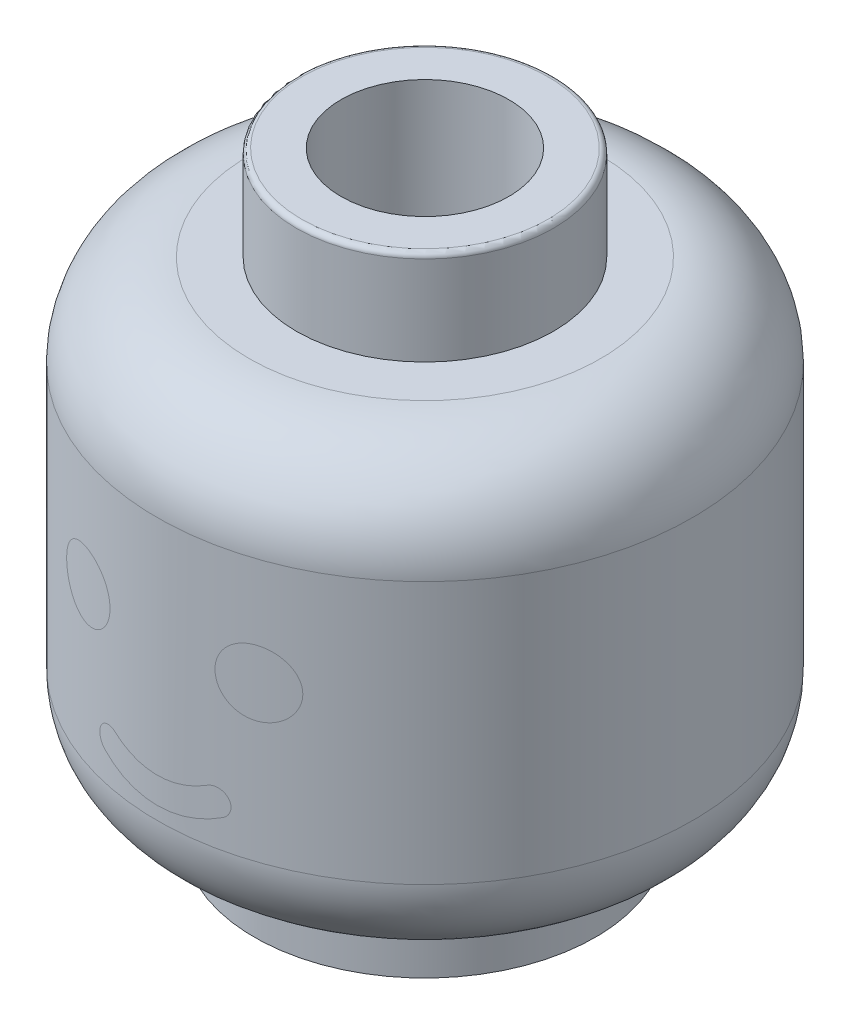
SolidWorks part; units mm, degrees
ref_plane "Plan de face" through (0, 0, 0) normal (0, 0, 1) x (1, 0, 0)
ref_plane "Plan de dessus" through (0, 0, 0) normal (0, 1, 0) x (1, 0, 0)
ref_plane "Plan de droite" through (0, 0, 0) normal (1, 0, 0) x (0, 0, -1)
sketch "Sketch2" plane through (0, 0, 0) normal (1, 0, 0) x (0, 0, -1)
  line L0 (0, 0) -> (0, 8.5) construction
  line L1 (2.45, 0) -> (3.25, 0)
  line L2 (3.25, 0) -> (3.25, 1.1)
  line L3 (3.25, 1.1) -> (3.35, 1.1)
  line L4 (5.1, 2.85) -> (5.1, 7.85)
  line L5 (3.35, 9.6) -> (2.45, 9.6)
  line L6 (2.45, 9.6) -> (2.45, 11.4)
  line L7 (2.45, 11.4) -> (0, 11.4)
  line L8 (0, 11.4) -> (0, 8.5)
  line L9 (0, 8.5) -> (2.45, 8.5)
  line L10 (2.45, 8.5) -> (2.45, 0)
  arc A0 (3.35, 1.1) -> (5.1, 2.85) centre (3.35, 2.85) ccw
  arc A1 (5.1, 7.85) -> (3.35, 9.6) centre (3.35, 7.85) ccw
  dimension "D8" = 1.75
  dimension "D1" = 2.45
  dimension "D2" = 0.8
  dimension "D3" = 2.65
  dimension "D4" = 1.1
  dimension "D5" = 9.6
  dimension "D6" = 1.8
  dimension "D7" = 2.9
revolve "Revolve1" add sketch "Sketch2" angle 360 about L0
sketch "Sketch3" plane through (0, 0, 0) normal (0, 0, 1) x (1, 0, 0)
  line L0 (-5.7474, 5.8) -> (6.0278, 5.8) construction
  line L1 (0, 0) -> (0, 6.7) construction
  line L2 (-5.7267, 3.1) -> (6.0487, 3.1) construction
  line L5 (-3.25, 0) -> (3.25, 0) construction
  line L6 (3.35, 9.6) -> (-3.35, 9.6) construction
  circle A0 centre (-1.625, 5.8) radius 0.625
  circle A1 centre (1.625, 5.8) radius 0.625
  arc A7 (-1, 3.6179) -> (1, 3.6179) centre (0, 5.35) ccw construction
  arc A8 (-1.125, 3.4014) -> (1.125, 3.4014) centre (0, 5.35) ccw
  arc A9 (-0.875, 3.8345) -> (0.875, 3.8345) centre (0, 5.35) ccw
  arc A10 (-0.875, 3.8345) -> (-1.125, 3.4014) centre (-1, 3.6179) ccw
  arc A11 (1.125, 3.4014) -> (0.875, 3.8345) centre (1, 3.6179) ccw
  point P26 (0, 3.35)
  dimension "D3" = 1.25
  dimension "D4" = 3.25
  dimension "D5" = 0.25
  dimension "D8" = 2
  dimension "D6" = 2
  dimension "D1" = 3.1
  dimension "D2" = 3.8
split line "Split Line1"
sketch "Sketch4" plane through (0, 11.4, 0) normal (0, 1, 0) x (1, 0, 0)
  circle A0 centre (0, 0) radius 1.6
  dimension "D1" = 3.2
extrude "Cut-Extrude1" cut sketch "Sketch4" against normal blind 2
sketch "Sketch5" plane through (0, 11.4, 0) normal (0, 1, 0) x (1, 0, 0)
  line L0 (0, 0) -> (0, 4.0991) construction
  line L1 (-1.547, -0.4082) -> (-0.42, 0.2425)
  line L2 (0, 0) -> (-2.2906, -1.3225) construction
  line L3 (-0.42, 0.2425) -> (-0.42, 1.5439)
  circle A0 centre (0, 0) radius 1.6 construction
  arc A1 (-0.42, 1.5439) -> (-1.547, -0.4082) centre (0, 0) ccw
  dimension "D1" = 120
  dimension "D2" = 0.42
  dimension "D3" = 0.42
extrude "Cut-Extrude2" cut sketch "Sketch5" against normal up to next
pattern_circular "CirPattern1" count 3 over 360 about axis through (0, 0, 0) along (0, 1, 0) of "Cut-Extrude2"
fillet "Fillet1" radius 0.1 1 edges at (0, 11.4, -2.45)
